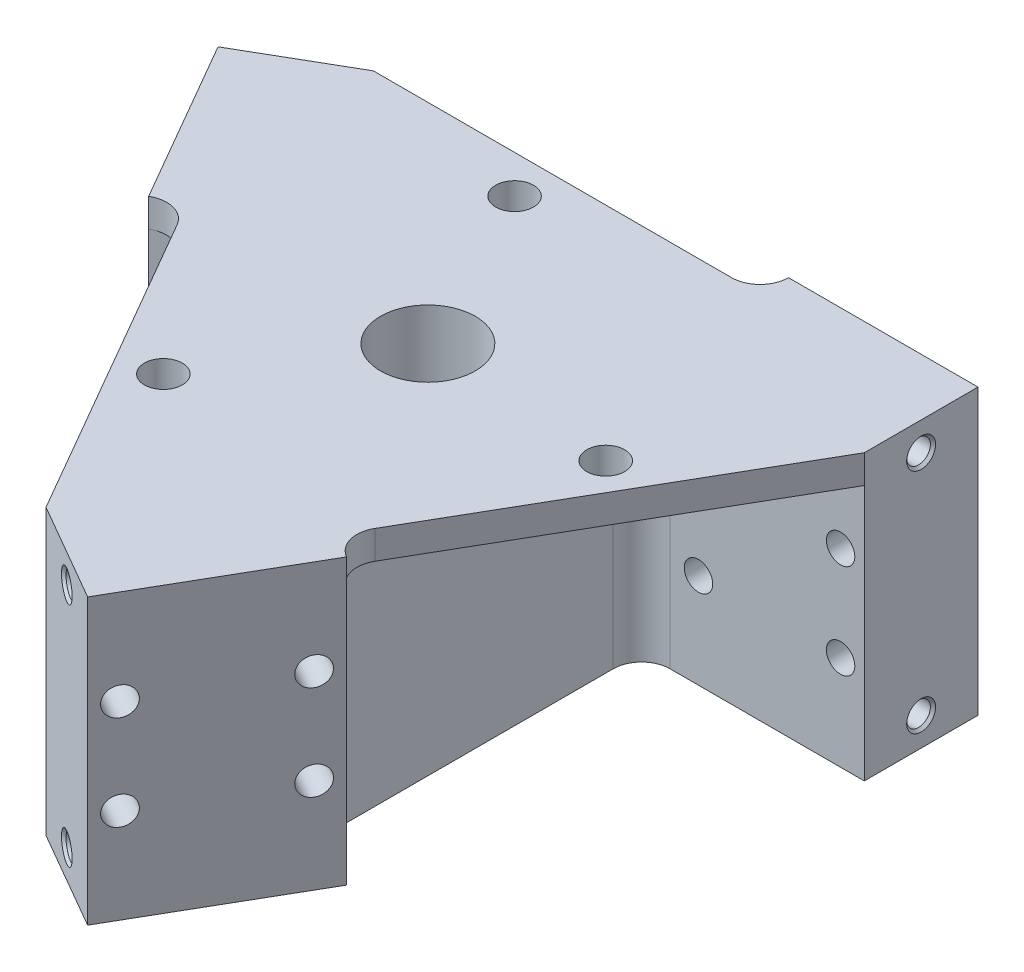
SolidWorks part; units mm, degrees
material "6061 合金"
ref_plane "Front" through (0, 0, 0) normal (0, 0, 1) x (1, 0, 0)
ref_plane "Top" through (0, 0, 0) normal (0, 1, 0) x (1, 0, 0)
ref_plane "Right" through (0, 0, 0) normal (1, 0, 0) x (0, 0, -1)
sketch "草图1" plane through (0, 0, 0) normal (0, 1, 0) x (1, 0, 0)
  line L0 (35, 55) -> (4.2781, 55) construction
  line L7 (20, 42.5) -> (50, 42.5) construction
  line L17 (0, 82.3386) -> (0, 0) construction
  line L18 (0, 0) -> (82.6038, -47.6913) construction
  line L19 (0, 0) -> (-42.2762, -24.4082) construction
  line L20 (20, 42.5) -> (20, 67.5) construction
  line L21 (-10, 87) -> (10, 87) construction
  line L22 (-10, 87) -> (-10, 23) construction
  line L23 (-10, 23) -> (10, 23) construction
  line L24 (10, 87) -> (10, 23) construction
  line L25 (-10, 87) -> (10, 23) construction
  line L26 (-10, 23) -> (10, 87) construction
  line L27 (20, 67.5) -> (50, 67.5) construction
  line L28 (50, 42.5) -> (50, 67.5) construction
  line L29 (20, 42.5) -> (50, 67.5) construction
  line L30 (20, 67.5) -> (50, 42.5) construction
  line L31 (20, 67.5) -> (20, 39.5) construction
  line L32 (17, 33.5) -> (35, 33.5) construction
  line L33 (35, 33.5) -> (35, 39.5) construction
  line L34 (35, 39.5) -> (20, 39.5) construction
  line L35 (17, 33.5) -> (17, 67.5) construction
  line L36 (17, 67.5) -> (20, 67.5) construction
  line L37 (30.1314, -57.8109) -> (45.4923, -31.205) construction
  line L38 (26.8061, -38.5705) -> (11.8061, -64.5513) construction
  line L39 (26.8061, -38.5705) -> (48.4567, -51.0705) construction
  line L40 (80.3442, -34.8397) -> (70.3442, -52.1603) construction
  line L41 (80.3442, -34.8397) -> (24.9186, -2.8397) construction
  line L42 (24.9186, -2.8397) -> (14.9186, -20.1603) construction
  line L43 (70.3442, -52.1603) -> (14.9186, -20.1603) construction
  line L44 (80.3442, -34.8397) -> (14.9186, -20.1603) construction
  line L45 (24.9186, -2.8397) -> (70.3442, -52.1603) construction
  line L46 (48.4567, -51.0705) -> (33.4567, -77.0513) construction
  line L47 (11.8061, -64.5513) -> (33.4567, -77.0513) construction
  line L48 (26.8061, -38.5705) -> (33.4567, -77.0513) construction
  line L49 (48.4567, -51.0705) -> (11.8061, -64.5513) construction
  line L50 (48.4567, -51.0705) -> (24.208, -37.0705) construction
  line L51 (24.208, -37.0705) -> (11.8937, -58.3995) construction
  line L52 (11.8937, -58.3995) -> (6.6976, -55.3995) construction
  line L53 (6.6976, -55.3995) -> (20.5119, -31.4724) construction
  line L54 (20.5119, -31.4724) -> (49.9567, -48.4724) construction
  line L55 (49.9567, -48.4724) -> (48.4567, -51.0705) construction
  line L56 (-65.1314, 2.8109) -> (-49.7705, -23.795) construction
  line L57 (-46.8061, -3.9295) -> (-61.8061, 22.0513) construction
  line L58 (-46.8061, -3.9295) -> (-68.4567, -16.4295) construction
  line L59 (-70.3442, -52.1603) -> (-80.3442, -34.8397) construction
  line L60 (-70.3442, -52.1603) -> (-14.9186, -20.1603) construction
  line L61 (-14.9186, -20.1603) -> (-24.9186, -2.8397) construction
  line L62 (-80.3442, -34.8397) -> (-24.9186, -2.8397) construction
  line L63 (-70.3442, -52.1603) -> (-24.9186, -2.8397) construction
  line L64 (-14.9186, -20.1603) -> (-80.3442, -34.8397) construction
  line L65 (-68.4567, -16.4295) -> (-83.4567, 9.5513) construction
  line L66 (-61.8061, 22.0513) -> (-83.4567, 9.5513) construction
  line L67 (-46.8061, -3.9295) -> (-83.4567, 9.5513) construction
  line L68 (-68.4567, -16.4295) -> (-61.8061, 22.0513) construction
  line L69 (-68.4567, -16.4295) -> (-44.208, -2.4295) construction
  line L70 (-44.208, -2.4295) -> (-49.6015, 6.9124) construction
  line L71 (-49.6015, 6.9124) -> (-44.4054, 9.9124) construction
  line L72 (-44.4054, 9.9124) -> (-37.5119, -2.0276) construction
  line L73 (-37.5119, -2.0276) -> (-66.9567, -19.0276) construction
  line L74 (-66.9567, -19.0276) -> (-68.4567, -16.4295) construction
  line L75 (33, 25.3) -> (13, 25.3)
  line L76 (13, 25.3) -> (13, 22.0513)
  line L77 (13, 22.0513) -> (-27.8061, 22.0513)
  line L79 (-38.4104, 15.9288) -> (-28.4104, -1.3917)
  line L80 (-28.4104, -1.3917) -> (-25.597, 0.2327)
  line L82 (5.4104, -41.2288) -> (15.4104, -23.9083)
  line L83 (15.4104, -23.9083) -> (12.597, -22.284)
  line L84 (12.597, -22.284) -> (33, 13.0551)
  line L87 (-5.1939, -35.1064) -> (-25.597, 0.2327)
  line L88 (10.4104, -32.5686) -> (17.5119, -36.6686) construction
  line L89 (6.0477, 5.9124) -> (0, 0) construction
  line L90 (0, 0) -> (2.2279, -8.7075) construction
  line L91 (0, 0) -> (-8.5407, 2.3924) construction
  line L92 (33, 25.3) -> (33, 13.0551)
  line L93 (-38.4104, 15.9288) -> (-27.8061, 22.0513)
  line L94 (5.4104, -41.2288) -> (-5.1939, -35.1064)
  line L95 (-33.4104, 7.2686) -> (-79.6416, -19.423) construction
  line L96 (23, 25.3) -> (23, 16.17) construction
  arc A0 (-47.6314, -27.5) -> (0, 55) centre (0, 0) ccw construction
  point P1 (35, 55)
  point P12 (30.1314, -57.8109)
  point P24 (0, 55)
  point P39 (47.6314, -27.5)
  point P44 (-65.1314, 2.8109)
  point P57 (-47.6314, -27.5)
  point P62 (0, 0)
  point P81 (13.6047, -43.436)
  dimension "D1" = 120
  dimension "D2" = 120
  dimension "D12" = 55
  dimension "D3" = 20
  dimension "D4" = 30
  dimension "D5" = 25
  dimension "D6" = 27
  dimension "D7" = 3
  dimension "D8" = 64
  dimension "D10" = 15
  dimension "D11" = 6
  dimension "D13" = 20
  dimension "D14" = 6
  dimension "D15" = 3
  dimension "D16" = 8.2
  dimension "D17" = 0.9487
  dimension "D18" = 6
  dimension "D19" = 8.2
  dimension "D20" = 8.2
  dimension "D21" = 6
  dimension "D25" = 120
  dimension "D26" = 120
  dimension "D9" = 3
extrude "凸台-拉伸1" add sketch "草图1" along normal blind 30
fillet "圆角3" radius 3 3 edges at (12.597, 15, 22.284) (-25.597, 15, -0.2327) (13, 15, -22.0513)
sketch "草图9" plane through (0, 0, 0) normal (0, -1, 0) x (1, 0, 0)
  circle A0 centre (0, 0) radius 5
  dimension "D1" = 10
extrude "切除-拉伸5" cut sketch "草图9" against normal through all
sketch "草图10" plane through (0, 0, 0) normal (0, -1, 0) x (1, 0, 0)
  line L0 (-27.8061, -22.0513) -> (-17.5561, -4.2977)
  line L1 (-13.458, -3.1997) -> (11.5, -17.6092)
  line L3 (13, -25.3) -> (13, -25.0513) construction
  line L6 (13, -20.2073) -> (13, -25.0513)
  line L7 (13, -25.3) -> (13, -25.0513) construction
  line L9 (13, -25.0513) -> (-27.8061, -22.0513)
  line L11 (-28.4104, 1.3917) -> (-28.195, 1.2673) construction
  arc A0 (13, -20.2073) -> (11.5, -17.6092) centre (10, -20.2073) ccw
  arc A1 (-17.5561, -4.2977) -> (-13.458, -3.1997) centre (-14.958, -5.7977) cw
  point P12 (12, -20.7846)
  point P15 (-16.0561, -1.6997)
  dimension "D2" = 3
  dimension "D3" = 3
  dimension "D1" = 3.5
extrude "切除-拉伸6" cut sketch "草图10" against normal offset from surface (27 mm away) 3 up to face at (0, 30, -5)
pattern_circular "阵列(圆周)1" count 3 over 360 about axis through (0, 0, 0) along (0, 1, 0) of "切除-拉伸6"
sketch "草图11" plane through (0, 0, 0) normal (0, -1, 0) x (1, 0, 0)
  line L0 (12.5, -13.0551) -> (33, -13.0551) construction
  line L1 (33, -25.3) -> (13, -25.3)
  line L2 (33, -25.3) -> (33, -25.0551)
  line L3 (33, -25.0551) -> (13, -25.0551)
  line L4 (13, -25.3) -> (13, -25.0551)
  dimension "D1" = 20
  dimension "D2" = 12
extrude "切除-拉伸7" cut sketch "草图11" against normal through all
sketch "草图12" plane through (0, 0, -13.0551) normal (0, 0, -1) x (-1, 0, 0)
  line L0 (-23, 0) -> (-23, 39.7058) construction
  line L1 (-33, 0) -> (-13, 0) construction
  line L4 (-15.5, 10) -> (-30.5, 10) construction
  line L5 (-15.5, 10) -> (-15.5, 20) construction
  line L6 (-15.5, 20) -> (-30.5, 20) construction
  line L7 (-30.5, 10) -> (-30.5, 20) construction
  line L8 (-15.5, 10) -> (-30.5, 20) construction
  line L9 (-15.5, 20) -> (-30.5, 10) construction
  line L10 (-33, 15) -> (-3.9381, 15) construction
  line L11 (-33, 30) -> (-33, 0) construction
  circle A0 centre (-30.5, 10) radius 1.5
  circle A1 centre (-30.5, 20) radius 1.5
  circle A2 centre (-15.5, 20) radius 1.5
  circle A3 centre (-15.5, 10) radius 1.5
  point P6 (-23, 15)
  dimension "D3" = 3
  dimension "D1" = 10
  dimension "D2" = 15
extrude "切除-拉伸8" cut sketch "草图12" along normal up to next
sketch "草图13" plane through (33, 0, 0) normal (1, 0, 0) x (0, 0, -1)
  line L0 (19.0551, 0) -> (19.0551, 41.9433) construction
  line L1 (13.0551, 0) -> (25.0551, 0) construction
  line L2 (13.0551, 30) -> (25.0551, 30) construction
  circle A0 centre (19.0551, 3) radius 1.25
  circle A1 centre (19.0551, 27) radius 1.25
  dimension "D1" = 2.5
  dimension "D2" = 3
  dimension "D3" = 3
hole_wizard "M3 螺纹孔1" positions "3D草图1" profile "草图14" tap size "M3" standard "GB"
sketch3d "3D草图1"
  point P0 (33, 3, -19.0551)
  point P3 (33, 27, -19.0551)
sketch "草图14" plane through (33, 3, -19.0551) normal (0, 1, 0) x (0, 0, -1)
  line L0 (0, 0) -> (0, 8.2511)
  line L1 (0, 8.2511) -> (1.25, 7.5)
  line L2 (1.25, 7.5) -> (1.25, 0.275)
  line L3 (1.25, 0.275) -> (1.525, 0)
  line L5 (1.525, 0) -> (0, 0)
  line L6 (-1.25, 0.275) -> (-1.525, 0) construction
  line L10 (0, 8.2511) -> (-1.25, 7.5) construction
  line L11 (0, -6.35) -> (0, 107.95) construction
  dimension "螺纹孔钻头直径" = 2.5
  dimension "螺纹孔钻头深度" = 7.5
  dimension "近端锥形沉头孔直径" = 3.05
  dimension "近端锥形沉头孔角度" = 90
  dimension "导头角度" = 118
cosmetic thread "孔螺蚊线1" parameters "D1"=6, "D2"=3
cosmetic thread "孔螺蚊线2" parameters "D1"=6, "D2"=3
pattern_circular "阵列(圆周)2" count 3 every 120 about axis through (0, 0, 0) along (0, 1, 0) of "切除-拉伸7", "切除-拉伸8", "M3 螺纹孔1"
sketch "草图15" plane through (0, 30, 0) normal (0, 1, 0) x (1, 0, 0)
  line L0 (-8.903, 22.0513) -> (-8.903, 0) construction
  line L1 (10, 22.0513) -> (-27.8061, 22.0513) construction
  line L2 (-14.6454, -18.7359) -> (-4.1376, -12.6692) construction
  line L3 (-24.097, -2.3654) -> (-5.1939, -35.1064) construction
  circle A1 centre (-8.903, 18.0513) radius 2
  circle A2 centre (20.0844, -1.3154) radius 2
  circle A3 centre (-11.1813, -16.7359) radius 2
  circle A4 centre (0, 0) radius 5 construction
  circle A5 centre (0, 0) radius 20.1274 construction
  point P13 (0, 0)
  dimension "D1" = 4
  dimension "D2" = 4
  dimension "D4" = 40.2548
  dimension "D3" = 3
extrude "切除-拉伸9" cut sketch "草图15" against normal through all
